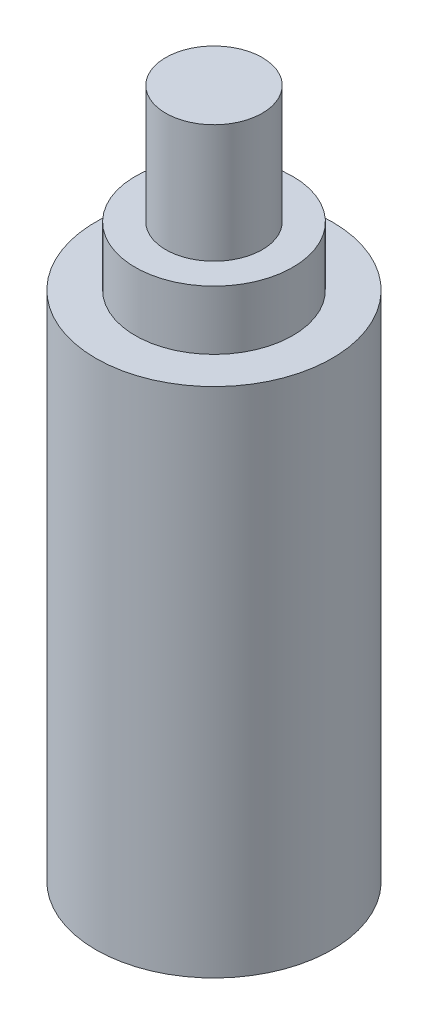
SolidWorks part; units mm, degrees
ref_plane "Front Plane" through (0, 0, 0) normal (0, 0, 1) x (1, 0, 0)
ref_plane "Top Plane" through (0, 0, 0) normal (0, 1, 0) x (1, 0, 0)
ref_plane "Right Plane" through (0, 0, 0) normal (1, 0, 0) x (0, 0, -1)
sketch "Sketch3" plane through (0, 0, 0) normal (0, 1, 0) x (1, 0, 0)
  line L0 (-15.24, 30.48) -> (-15.24, 0) construction
  line L5 (-30.48, 15.24) -> (0, 15.24) construction
  circle A0 centre (-15.24, 15.24) radius 7.62
  dimension "D3" = 15.24
extrude "Boss-Extrude1" add sketch "Sketch3" along normal blind 33.02
sketch "Sketch4" plane through (0, 33.02, 0) normal (0, 1, 0) x (1, 0, 0)
  circle A0 centre (-15.24, 15.24) radius 5.08
  dimension "D1" = 10.16
  dimension "D2" = 10.16
  dimension "D4" = 21.5526
  dimension "D3" = 15.24
extrude "Boss-Extrude2" add sketch "Sketch4" along normal blind 3.81
sketch "Sketch5" plane through (0, 36.83, 0) normal (0, 1, 0) x (1, 0, 0)
  circle A0 centre (-15.24, 15.24) radius 3.1115
  circle A1 centre (-15.24, 15.24) radius 5.08 construction
  circle A2 centre (-15.24, 15.24) radius 5.08 construction
  dimension "D1" = 6.223
extrude "Boss-Extrude3" add sketch "Sketch5" along normal blind 7.62
